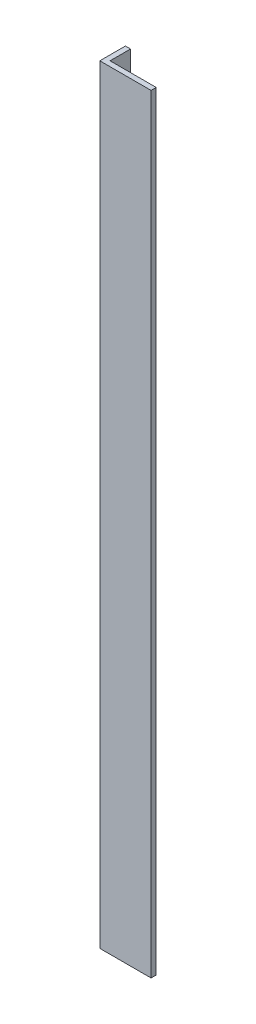
SolidWorks part; units mm, degrees
ref_plane "Front Plane" through (0, 0, 0) normal (0, 0, 1) x (1, 0, 0)
ref_plane "Top Plane" through (0, 0, 0) normal (0, 1, 0) x (1, 0, 0)
ref_plane "Right Plane" through (0, 0, 0) normal (1, 0, 0) x (0, 0, -1)
sketch "Sketch1" plane through (0, 0, 0) normal (0, 1, 0) x (1, 0, 0)
  line L0 (0, 0) -> (0, 10)
  line L1 (0, 10) -> (2, 10)
  line L2 (2, 10) -> (2, 2)
  line L3 (2, 2) -> (20, 2)
  line L4 (20, 2) -> (20, 0)
  line L5 (20, 0) -> (0, 0)
extrude "Boss-Extrude1" add sketch "Sketch1" along normal blind 300
hole_wizard "Ø3.0mm Dowel Hole1" positions "Sketch3" profile "Sketch5" hole size "Ø3.0" standard "ISO" end condition up to next
sketch "Sketch3" plane through (0, 0, 0) normal (-1, 0, 0) x (0, 0, 1)
  point P0 (-7.25, 2.75)
  point P3 (-7.25, 2.75)
sketch "Sketch5" plane through (0, 2.75, -7.25) normal (0, 1, 0) x (0, 0, 1)
  line L0 (0, 0) -> (0, 2)
  line L1 (0, 2) -> (1.5, 2)
  line L2 (1.5, 2) -> (1.5, 0)
  line L5 (1.5, 0) -> (0, 0)
  line L11 (0, -6.35) -> (0, 107.95) construction
  dimension "Thru Hole Dia." = 3
  dimension "Thru Hole Depth" = 2
hole_wizard "Ø3.0mm Dowel Hole2" positions "Sketch6" profile "Sketch7" hole size "Ø3.0" standard "ISO" end condition up to next
sketch "Sketch6" plane through (0, 0, 0) normal (-1, 0, 0) x (0, 0, 1)
  point P0 (-7.25, 211.25)
sketch "Sketch7" plane through (0, 211.25, -7.25) normal (0, 1, 0) x (0, 0, 1)
  line L0 (0, 0) -> (0, 2)
  line L1 (0, 2) -> (1.5, 2)
  line L2 (1.5, 2) -> (1.5, 0)
  line L5 (1.5, 0) -> (0, 0)
  line L11 (0, -6.35) -> (0, 107.95) construction
  dimension "Thru Hole Dia." = 3
  dimension "Thru Hole Depth" = 2
hole_wizard "Ø3.0 (3) Diameter Hole1" positions "Sketch8" profile "Sketch9" hole size "Ø3.0" standard "ISO"
sketch "Sketch8" plane through (2, 325.4076, 141.138) normal (1, 0, 0) x (0, 0, 1)
  point P0 (-147.138, 37.4076)
  point P1 (-147.138, 61.4076)
sketch "Sketch9" plane through (2, 288, -6) normal (0, 1, 0) x (0, 0, -1)
  line L0 (0, 0) -> (0, 2)
  line L1 (0, 2) -> (1.5, 2)
  line L2 (1.5, 2) -> (1.5, 0)
  line L3 (1.5, 0) -> (0, 0)
  line L4 (0, -6.35) -> (0, 107.95) construction
  dimension "Thru Hole Dia." = 3
  dimension "Thru Hole Depth" = 2
